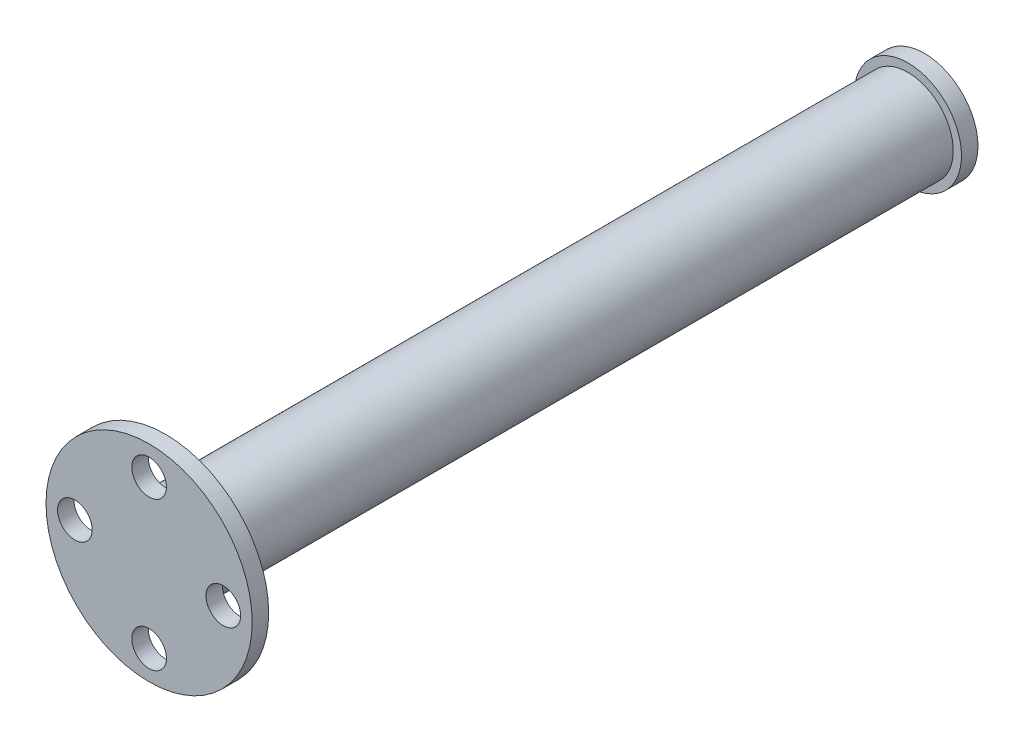
SolidWorks part; units mm, degrees
material "2024-O"
ref_plane "Front Plane" through (0, 0, 0) normal (0, 0, 1) x (1, 0, 0)
ref_plane "Top Plane" through (0, 0, 0) normal (0, 1, 0) x (1, 0, 0)
ref_plane "Right Plane" through (0, 0, 0) normal (1, 0, 0) x (0, 0, -1)
sketch "Sketch1" plane through (0, 0, 0) normal (0, 0, 1) x (1, 0, 0)
  circle A0 centre (0, 0) radius 6.5
  circle A1 centre (0, 0) radius 2.5
  dimension "D1" = 13
  dimension "D2" = 4
extrude "Boss-Extrude1" add sketch "Sketch1" along normal blind 2
sketch "Sketch2" plane through (0, 0, 2) normal (0, 0, 1) x (1, 0, 0)
  circle A2 centre (0, 0) radius 5.5
  circle A3 centre (0, 0) radius 3.5
  circle A4 centre (0, 0) radius 3.5
  dimension "D1" = 1
  dimension "D2" = 2
extrude "Boss-Extrude2" add sketch "Sketch2" along normal blind 90
sketch "Sketch4" plane through (0, 0, 92) normal (0, 0, 1) x (1, 0, 0)
  circle A1 centre (0, 0) radius 3.5
  dimension "D3" = 7
extrude "Boss-Extrude3" add sketch "Sketch4" against normal blind 2
sketch "Sketch5" plane through (0, 0, 92) normal (0, 0, 1) x (1, 0, 0)
  circle A0 centre (0, 0) radius 12.5
  dimension "D1" = 25
extrude "Boss-Extrude4" add sketch "Sketch5" along normal blind 2
sketch "Sketch6" plane through (0, 0, 92) normal (0, 0, -1) x (-1, 0, 0)
  line L0 (0, 0) -> (0, 9) construction
  circle A0 centre (0, 9) radius 2.1
  circle A1 centre (9, 0) radius 2.1
  circle A2 centre (0, -9) radius 2.1
  circle A3 centre (-9, 0) radius 2.1
  point P13 (0, 0)
  dimension "D2" = 4.2
  dimension "D1" = 9
  dimension "D3" = 4
extrude "Cut-Extrude1" cut sketch "Sketch6" against normal blind 10
equation "\"diam externo\"= 25 - 12"
equation "\"D1@Sketch1\"=\"diam externo\""
equation "\"comprimento tubo\"= 90"
equation "\"D1@Boss-Extrude2\"=\"comprimento tubo\""
equation "\"diametro externo\"= 24.8"
